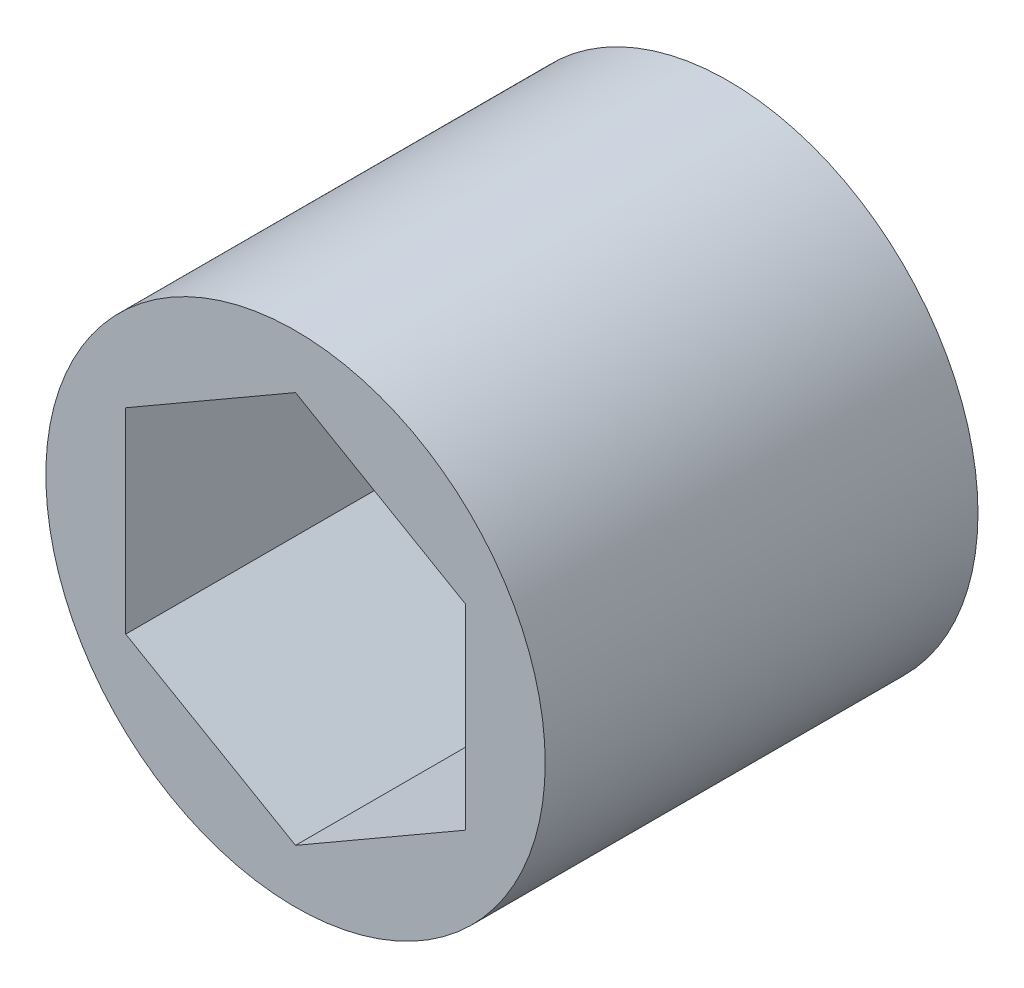
SolidWorks part; units mm, degrees
material "PET"
ref_plane "Front Plane" through (0, 0, 0) normal (0, 0, 1) x (1, 0, 0)
ref_plane "Top Plane" through (0, 0, 0) normal (0, 1, 0) x (1, 0, 0)
ref_plane "Right Plane" through (0, 0, 0) normal (1, 0, 0) x (0, 0, -1)
sketch "Sketch1" plane through (0, 0, 0) normal (0, 0, 1) x (1, 0, 0)
  line L1 (0, 7.479) -> (-6.477, 3.7395)
  line L2 (-6.477, 3.7395) -> (-6.477, -3.7395)
  line L3 (-6.477, -3.7395) -> (0, -7.479)
  line L4 (0, -7.479) -> (6.477, -3.7395)
  line L5 (6.477, -3.7395) -> (6.477, 3.7395)
  line L6 (6.477, 3.7395) -> (0, 7.479)
  circle A0 centre (0, 0) radius 9.525
  circle A1 centre (0, 0) radius 6.477 construction
  dimension "D1" = 12.954
  dimension "D2" = 19.05
extrude "Boss-Extrude1" add sketch "Sketch1" along normal mid plane 16.51
